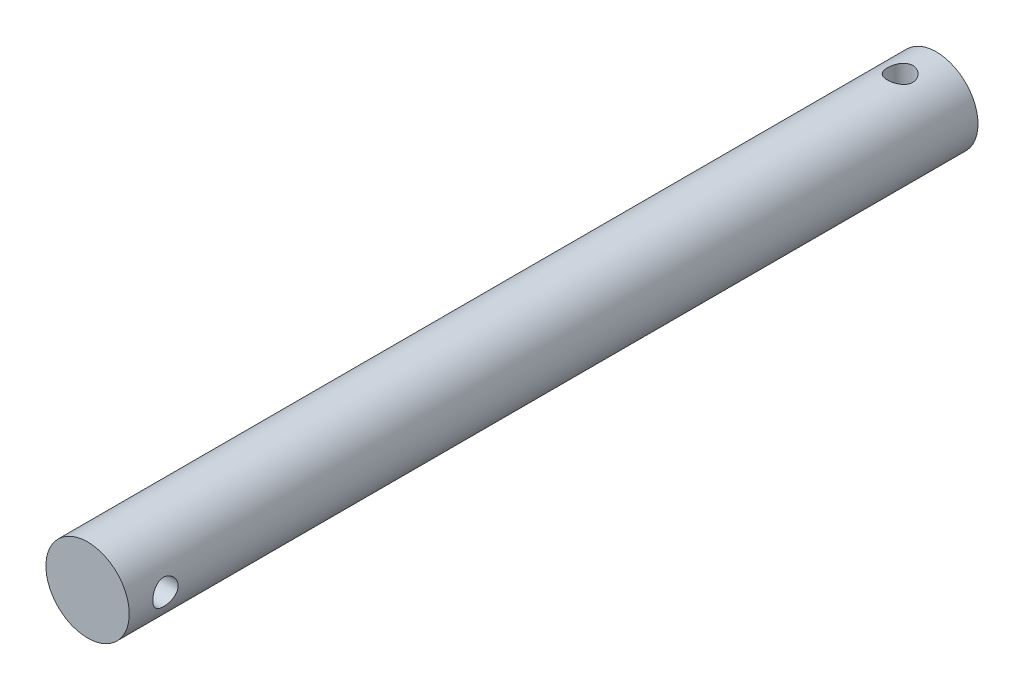
SolidWorks part; units mm, degrees
ref_plane "Front Plane" through (0, 0, 0) normal (0, 0, 1) x (1, 0, 0)
ref_plane "Top Plane" through (0, 0, 0) normal (0, 1, 0) x (1, 0, 0)
ref_plane "Right Plane" through (0, 0, 0) normal (1, 0, 0) x (0, 0, -1)
sketch "Sketch3" plane through (0, 0, 0) normal (0, 0, 1) x (1, 0, 0)
  circle A0 centre (0, 0) radius 5.75
  dimension "D1" = 11.5
extrude "Boss-Extrude1" add sketch "Sketch3" along normal blind 117.15
sketch "Sketch4" plane through (0, 0, 0) normal (0, 1, 0) x (1, 0, 0)
  line L0 (0, -5) -> (0, 0) construction
  circle A0 centre (0, -5) radius 1.75
  dimension "D2" = 3.5
  dimension "D1" = 5
ref_plane "Plane1" through (0, 0, 58.575) normal (0, 0, -1) x (-1, 0, 0)
extrude "Cut-Extrude2" cut sketch "Sketch4" along normal mid plane 30
sketch "Sketch5" plane through (0, 0, 0) normal (1, 0, 0) x (0, 0, -1)
  line L0 (-117.15, 0) -> (-112.15, 0)
  line L1 (-117.15, 5.75) -> (-117.15, -5.75) construction
  circle A0 centre (-112.15, 0) radius 1.75
  dimension "D2" = 3.5
  dimension "D1" = 5
extrude "Cut-Extrude3" cut sketch "Sketch5" against normal mid plane 30
